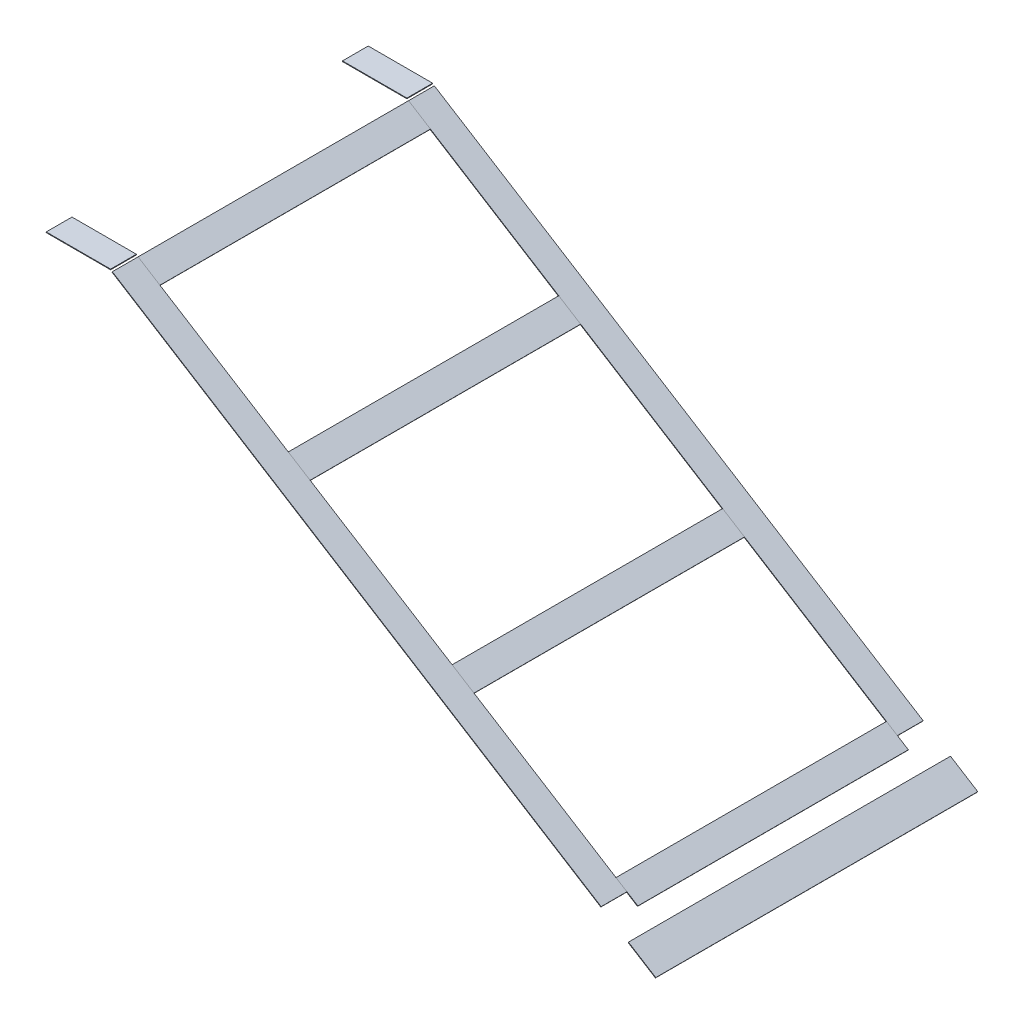
SolidWorks part; units mm, degrees
ref_plane "前视基准面" through (0, 0, 0) normal (0, 0, 1) x (1, 0, 0)
ref_plane "上视基准面" through (0, 0, 0) normal (0, 1, 0) x (1, 0, 0)
ref_plane "右视基准面" through (0, 0, 0) normal (1, 0, 0) x (0, 0, -1)
other "Configuration Table"
sketch "草图1" plane through (0, 0, 0) normal (0, 0, 1) x (1, 0, 0)
  line L0 (152.6505, 557.5584) -> (911.6535, 83.2806)
  line L1 (911.6535, 83.2806) -> (911.1236, 82.4326)
  line L2 (911.1236, 82.4326) -> (152.1206, 556.7103)
  line L3 (152.1206, 556.7103) -> (152.6505, 557.5584)
extrude "Rail_seat_1_EPDM_t1" add sketch "草图1" along normal blind 40 separate body
sketch "草图2" plane through (0, 0, 0) normal (0, 0, 1) x (1, 0, 0)
  line L0 (50, 558.7521) -> (150, 558.7521)
  line L1 (150, 558.7521) -> (150, 559.7521)
  line L2 (150, 559.7521) -> (50, 559.7521)
  line L3 (50, 559.7521) -> (50, 558.7521)
extrude "Platform_seat_1_EPDM_t1" add sketch "草图2" along normal blind 40 separate body
sketch "草图3" plane through (0, 0, 0) normal (0, 0, 1) x (1, 0, 0)
  line L0 (152.6505, 557.5584) -> (911.6535, 83.2806)
  line L1 (911.6535, 83.2806) -> (911.1236, 82.4326)
  line L2 (911.1236, 82.4326) -> (152.1206, 556.7103)
  line L3 (152.1206, 556.7103) -> (152.6505, 557.5584)
extrude "Rail_seat_2_EPDM_t1" add sketch "草图3" along normal blind 40 from offset 460 separate body
sketch "草图4" plane through (0, 0, 0) normal (0, 0, 1) x (1, 0, 0)
  line L0 (50, 558.7521) -> (150, 558.7521)
  line L1 (150, 558.7521) -> (150, 559.7521)
  line L2 (150, 559.7521) -> (50, 559.7521)
  line L3 (50, 559.7521) -> (50, 558.7521)
extrude "Platform_seat_2_EPDM_t1" add sketch "草图4" along normal blind 40 from offset 460 separate body
sketch "草图5" plane through (0, 0, 0) normal (0, 0, 1) x (1, 0, 0)
  line L0 (954.0559, 56.7847) -> (996.4583, 30.2887)
  line L1 (996.4583, 30.2887) -> (995.9284, 29.4407)
  line L2 (995.9284, 29.4407) -> (953.526, 55.9366)
  line L3 (953.526, 55.9366) -> (954.0559, 56.7847)
extrude "Toe_seat_EPDM_t1" add sketch "草图5" along normal blind 500 separate body
sketch "草图6" plane through (0, 0, 0) normal (0, 0, 1) x (1, 0, 0)
  line L0 (152.6505, 557.5584) -> (186.5724, 536.3616)
  line L1 (186.5724, 536.3616) -> (186.0425, 535.5136)
  line L2 (186.0425, 535.5136) -> (152.1206, 556.7103)
  line L3 (152.1206, 556.7103) -> (152.6505, 557.5584)
extrude "Cross_seat_s25_EPDM_t1" add sketch "草图6" along normal blind 420 from offset 40 separate body
sketch "草图7" plane through (0, 0, 0) normal (0, 0, 1) x (1, 0, 0)
  line L0 (385.8637, 411.8306) -> (419.7856, 390.6338)
  line L1 (419.7856, 390.6338) -> (419.2557, 389.7858)
  line L2 (419.2557, 389.7858) -> (385.3338, 410.9825)
  line L3 (385.3338, 410.9825) -> (385.8637, 411.8306)
extrude "Cross_seat_s300_EPDM_t1" add sketch "草图7" along normal blind 420 from offset 40 separate body
sketch "草图8" plane through (0, 0, 0) normal (0, 0, 1) x (1, 0, 0)
  line L0 (640.2781, 252.8548) -> (674.2001, 231.658)
  line L1 (674.2001, 231.658) -> (673.6701, 230.81)
  line L2 (673.6701, 230.81) -> (639.7482, 252.0068)
  line L3 (639.7482, 252.0068) -> (640.2781, 252.8548)
extrude "Cross_seat_s600_EPDM_t1" add sketch "草图8" along normal blind 420 from offset 40 separate body
sketch "草图9" plane through (0, 0, 0) normal (0, 0, 1) x (1, 0, 0)
  line L0 (894.6926, 93.879) -> (928.6145, 72.6823)
  line L1 (928.6145, 72.6823) -> (928.0846, 71.8342)
  line L2 (928.0846, 71.8342) -> (894.1626, 93.031)
  line L3 (894.1626, 93.031) -> (894.6926, 93.879)
extrude "Cross_seat_s900_EPDM_t1" add sketch "草图9" along normal blind 420 from offset 40 separate body
